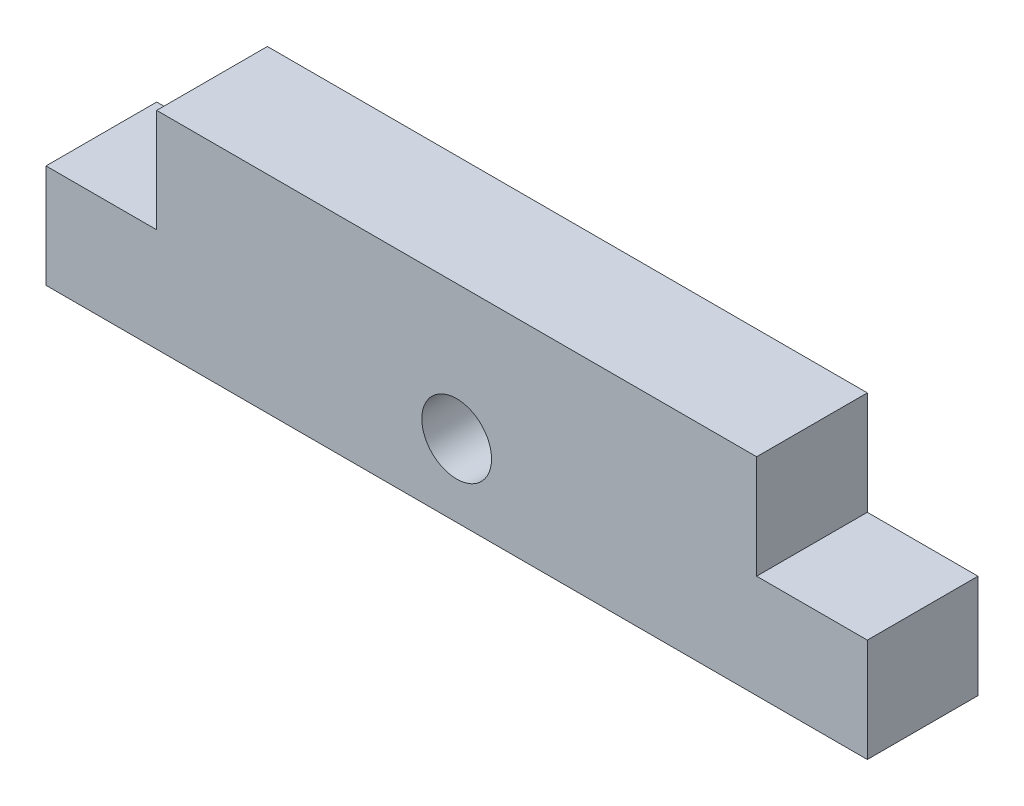
SolidWorks part; units mm, degrees
ref_plane "Front Plane" through (0, 0, 0) normal (0, 0, 1) x (1, 0, 0)
ref_plane "Top Plane" through (0, 0, 0) normal (0, 1, 0) x (1, 0, 0)
ref_plane "Right Plane" through (0, 0, 0) normal (1, 0, 0) x (0, 0, -1)
sketch "Model" plane through (0, 0, 0) normal (0, 0, 1) x (1, 0, 0)
  line L647 (5.35, 10) -> (5.35, 5)
  line L648 (34.35, 10) -> (5.35, 10)
  line L649 (34.35, 5) -> (34.35, 10)
  line L650 (39.7, 5) -> (34.35, 5)
  line L651 (39.7, 0) -> (39.7, 5)
  line L652 (0, 0) -> (39.7, 0)
  line L653 (0, 5) -> (0, 0)
  line L654 (5.35, 5) -> (0, 5)
  circle A164 centre (19.85, 3.5) radius 1.685
extrude "Boss-Extrude1" add sketch "Model" along normal blind 5.35
